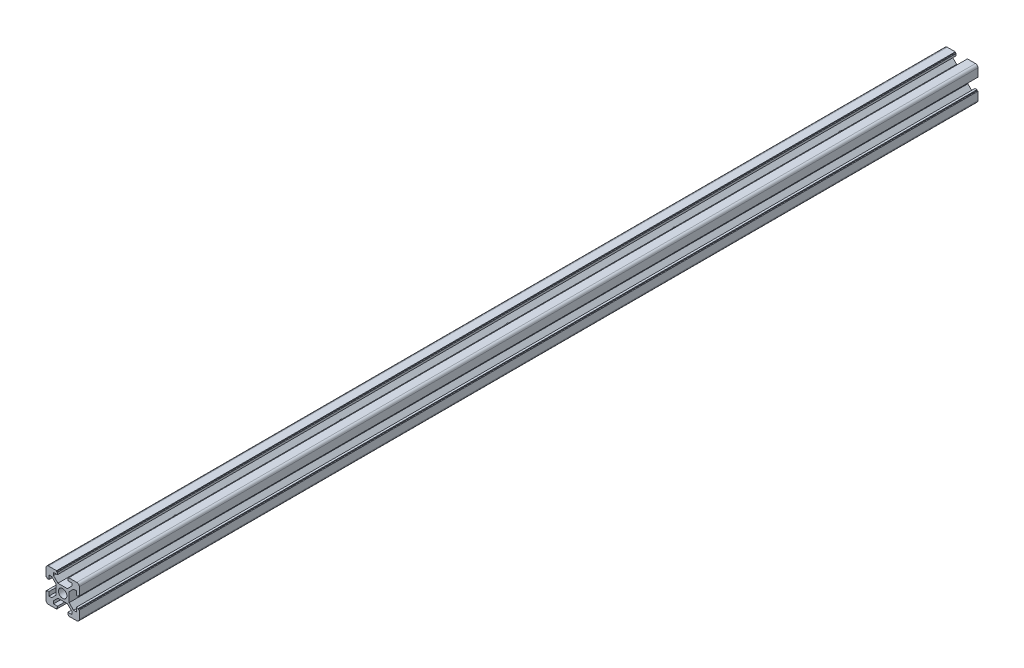
SolidWorks part; units mm, degrees
material "6063-T5"
ref_plane "前视基准面" through (0, 0, 0) normal (0, 0, 1) x (1, 0, 0)
ref_plane "上视基准面" through (0, 0, 0) normal (0, 1, 0) x (1, 0, 0)
ref_plane "右视基准面" through (0, 0, 0) normal (1, 0, 0) x (0, 0, -1)
sketch "草图2" plane through (0, 0, 0) normal (0, 0, 1) x (1, 0, 0)
  line L0 (-3.9, 2.8393) -> (-6.5607, 5.5)
  line L1 (-2.8393, 3.9) -> (2.8393, 3.9)
  line L2 (-3.9, 2.8393) -> (-3.9, -2.8393)
  line L3 (-2.8393, -3.9) -> (2.8393, -3.9)
  line L4 (3.9, 2.8393) -> (3.9, -2.8393)
  line L5 (-3.9, 3.9) -> (3.9, -3.9) construction
  line L6 (-3.9, -3.9) -> (3.9, 3.9) construction
  line L7 (-2.8393, 3.9) -> (-5.5, 6.5607)
  line L8 (-5.5, 6.5607) -> (-5.5, 8.2)
  line L9 (-5.5, 8.2) -> (-3.1, 8.2)
  line L10 (-3.1, 8.2) -> (-3.1, 9.45)
  line L11 (-3.1, 9.45) -> (-3.65, 9.45)
  line L12 (-3.65, 9.45) -> (-3.65, 10)
  line L13 (-3.65, 10) -> (-8.5, 10)
  line L14 (-6.5607, 5.5) -> (-8.2, 5.5)
  line L15 (-10, 3.65) -> (-10, 8.5)
  line L16 (-9.45, 3.65) -> (-10, 3.65)
  line L17 (-9.45, 3.1) -> (-9.45, 3.65)
  line L18 (-8.2, 3.1) -> (-9.45, 3.1)
  line L19 (-8.2, 5.5) -> (-8.2, 3.1)
  line L20 (2.8393, 3.9) -> (5.5, 6.5607)
  line L21 (3.9, 2.8393) -> (6.5607, 5.5)
  line L22 (6.5607, 5.5) -> (8.2, 5.5)
  line L23 (8.2, 5.5) -> (8.2, 3.1)
  line L24 (8.2, 3.1) -> (9.45, 3.1)
  line L25 (9.45, 3.1) -> (9.45, 3.65)
  line L26 (9.45, 3.65) -> (10, 3.65)
  line L27 (10, 3.65) -> (10, 8.5)
  line L28 (5.5, 6.5607) -> (5.5, 8.2)
  line L29 (3.65, 10) -> (8.5, 10)
  line L30 (3.65, 9.45) -> (3.65, 10)
  line L31 (3.1, 9.45) -> (3.65, 9.45)
  line L32 (3.1, 8.2) -> (3.1, 9.45)
  line L33 (5.5, 8.2) -> (3.1, 8.2)
  line L34 (3.9, -2.8393) -> (6.5607, -5.5)
  line L35 (2.8393, -3.9) -> (5.5, -6.5607)
  line L36 (5.5, -6.5607) -> (5.5, -8.2)
  line L37 (5.5, -8.2) -> (3.1, -8.2)
  line L38 (3.1, -8.2) -> (3.1, -9.45)
  line L39 (3.1, -9.45) -> (3.65, -9.45)
  line L40 (3.65, -9.45) -> (3.65, -10)
  line L41 (3.65, -10) -> (8.5, -10)
  line L42 (6.5607, -5.5) -> (8.2, -5.5)
  line L43 (10, -3.65) -> (10, -8.5)
  line L44 (9.45, -3.65) -> (10, -3.65)
  line L45 (9.45, -3.1) -> (9.45, -3.65)
  line L46 (8.2, -3.1) -> (9.45, -3.1)
  line L47 (8.2, -5.5) -> (8.2, -3.1)
  line L48 (-2.8393, -3.9) -> (-5.5, -6.5607)
  line L49 (-3.9, -2.8393) -> (-6.5607, -5.5)
  line L50 (-6.5607, -5.5) -> (-8.2, -5.5)
  line L51 (-8.2, -5.5) -> (-8.2, -3.1)
  line L52 (-8.2, -3.1) -> (-9.45, -3.1)
  line L53 (-9.45, -3.1) -> (-9.45, -3.65)
  line L54 (-9.45, -3.65) -> (-10, -3.65)
  line L55 (-10, -3.65) -> (-10, -8.5)
  line L56 (-5.5, -6.5607) -> (-5.5, -8.2)
  line L57 (-3.65, -10) -> (-8.5, -10)
  line L58 (-3.65, -9.45) -> (-3.65, -10)
  line L59 (-3.1, -9.45) -> (-3.65, -9.45)
  line L60 (-3.1, -8.2) -> (-3.1, -9.45)
  line L61 (-5.5, -8.2) -> (-3.1, -8.2)
  circle A0 centre (0, 0) radius 2.55
  arc A1 (-8.5, 10) -> (-10, 8.5) centre (-8.5, 8.5) ccw
  arc A2 (10, 8.5) -> (8.5, 10) centre (8.5, 8.5) ccw
  arc A3 (8.5, -10) -> (10, -8.5) centre (8.5, -8.5) ccw
  arc A4 (-10, -8.5) -> (-8.5, -10) centre (-8.5, -8.5) ccw
  point P25 (-10, 10)
  point P79 (0, 0)
  dimension "D1" = 5.1
  dimension "D9" = 1.5
  dimension "D2" = 7.8
  dimension "D3" = 1.5
  dimension "D4" = 10
  dimension "D5" = 3.1
  dimension "D6" = 0.55
  dimension "D7" = 1.8
  dimension "D8" = 5.5
  dimension "D11" = 3.9
  dimension "D10" = 4
extrude "凸台-拉伸1" add sketch "草图2" along normal blind 540
sketch "草图4" plane through (0, -10, 0) normal (0, -1, 0) x (1, 0, 0)
  line L0 (0, 540) -> (0, 0) construction
  line L1 (-2.8393, 540) -> (2.8393, 540) construction
  circle A0 centre (0, 270) radius 3
  circle A1 centre (0, 170) radius 3
  circle A2 centre (0, 370) radius 3
  circle A3 centre (0, 470) radius 3
  circle A4 centre (0, 70) radius 3
  dimension "D1" = 6
  dimension "D2" = 6
  dimension "D3" = 6
  dimension "D6" = 6
  dimension "D8" = 6
  dimension "D4" = 100
  dimension "D5" = 100
  dimension "D7" = 100
  dimension "D9" = 100
extrude "切除-拉伸2" cut sketch "草图4" against normal blind 20
